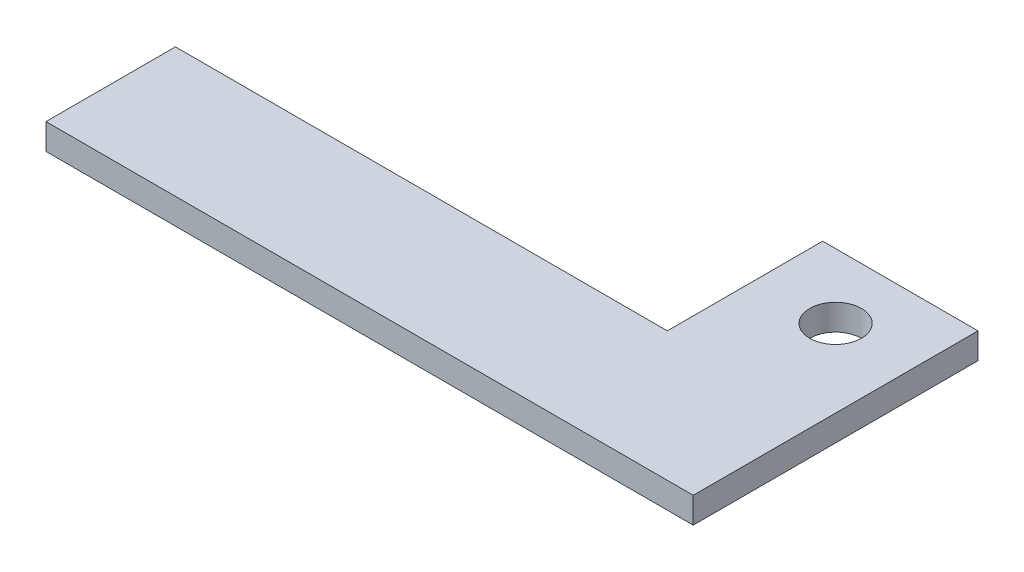
SolidWorks part; units mm, degrees
material "1060 Alloy"
ref_plane "Front Plane" through (0, 0, 0) normal (0, 0, 1) x (1, 0, 0)
ref_plane "Top Plane" through (0, 0, 0) normal (0, 1, 0) x (1, 0, 0)
ref_plane "Right Plane" through (0, 0, 0) normal (1, 0, 0) x (0, 0, -1)
sketch "Sketch1" plane through (0, 0, 0) normal (0, 1, 0) x (1, 0, 0)
  line L0 (0, 0) -> (-50, 0)
  line L1 (-50, 0) -> (-50, 10)
  line L2 (-50, 10) -> (-12, 10)
  line L3 (-12, 10) -> (-12, 22)
  line L4 (-12, 22) -> (0, 22)
  line L5 (0, 22) -> (0, 0)
  line L6 (-6, 17) -> (-6, 22) construction
  circle A0 centre (-6, 17) radius 2
  dimension "D2" = 4
  dimension "D1" = 12
  dimension "D3" = 22
  dimension "D4" = 5
  dimension "D5" = 10
  dimension "D6" = 50
extrude "Boss-Extrude1" add sketch "Sketch1" along normal blind 2
